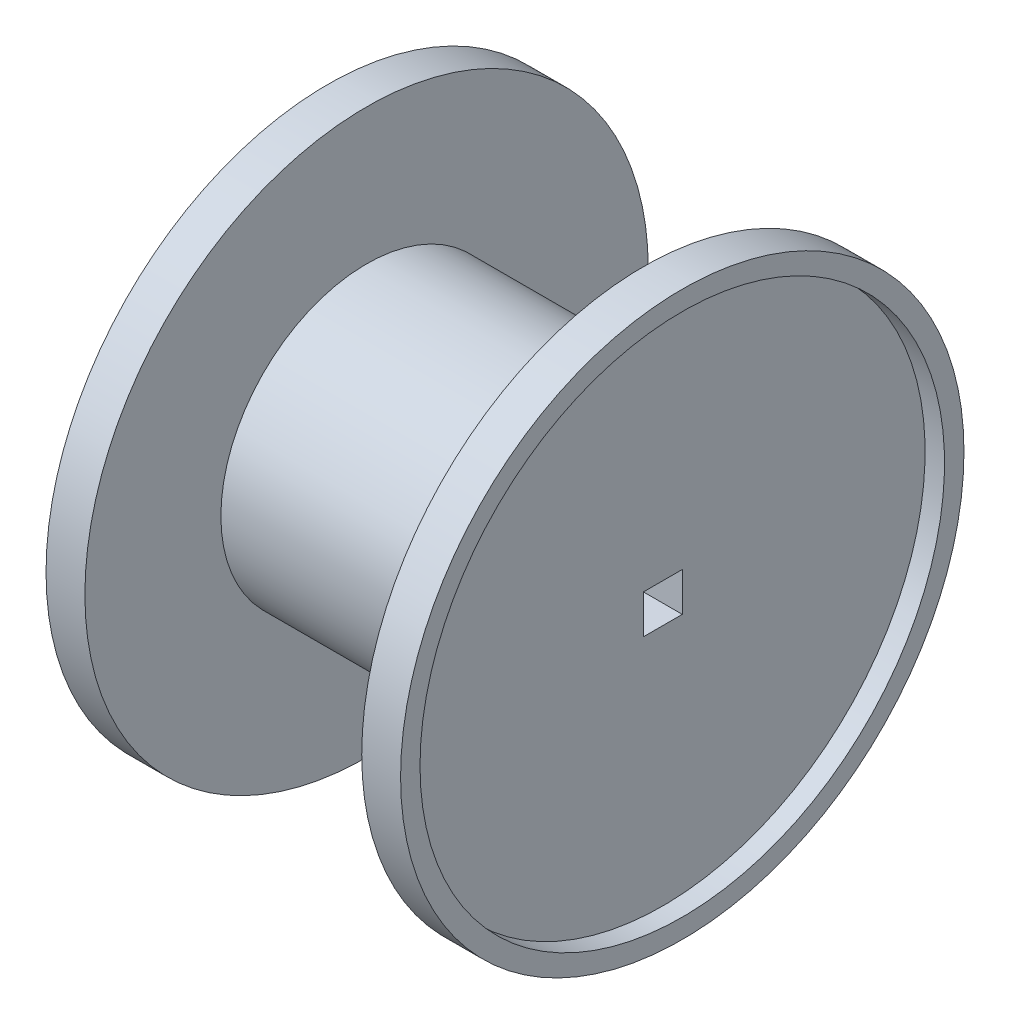
SolidWorks part; units mm, degrees
ref_plane "Plan de face" through (0, 0, 0) normal (0, 0, 1) x (1, 0, 0)
ref_plane "Plan de dessus" through (0, 0, 0) normal (0, 1, 0) x (1, 0, 0)
ref_plane "Plan de droite" through (0, 0, 0) normal (1, 0, 0) x (0, 0, -1)
sketch "Esquisse1" plane through (0, 0, 0) normal (0, 0, 1) x (1, 0, 0)
  line L0 (0, 0) -> (373.5631, 0) construction
  line L1 (0, 0) -> (0, 290)
  line L2 (0, 290) -> (20, 290)
  line L3 (20, 290) -> (20, 150)
  line L4 (305, 150) -> (305, 290)
  line L7 (20, 150) -> (305, 150)
  line L9 (305, 290) -> (325, 290)
  line L10 (325, 290) -> (325, 0)
  line L11 (0, 0) -> (325, 0)
  line L13 (325, 290) -> (345, 290)
  line L14 (325, 290) -> (325, 270)
  line L15 (325, 270) -> (345, 270)
  line L16 (345, 290) -> (345, 270)
  line L17 (0, 290) -> (-20, 290)
  line L18 (0, 290) -> (0, 270)
  line L19 (0, 270) -> (-20, 270)
  line L20 (-20, 290) -> (-20, 270)
  dimension "D2" = 300
  dimension "D3" = 20
  dimension "D4" = 285
  dimension "D5" = 580
  dimension "D6" = 20
  dimension "D7" = 20
  dimension "D8" = 20
revolve "Révolution1" add sketch "Esquisse1" angle 360 about L0
sketch "Esquisse2" plane through (0, 0, 0) normal (-1, 0, 0) x (0, 0, 1)
  line L0 (-20, 20) -> (20, -20) construction
  line L1 (-20, 20) -> (20, 20)
  line L2 (-20, 20) -> (-20, -20)
  line L3 (-20, -20) -> (20, -20)
  line L4 (20, 20) -> (20, -20)
  point P4 (0, 0)
  dimension "D1" = 40
extrude "Enlèv. mat.-Extru.1" cut sketch "Esquisse2" against normal through all
